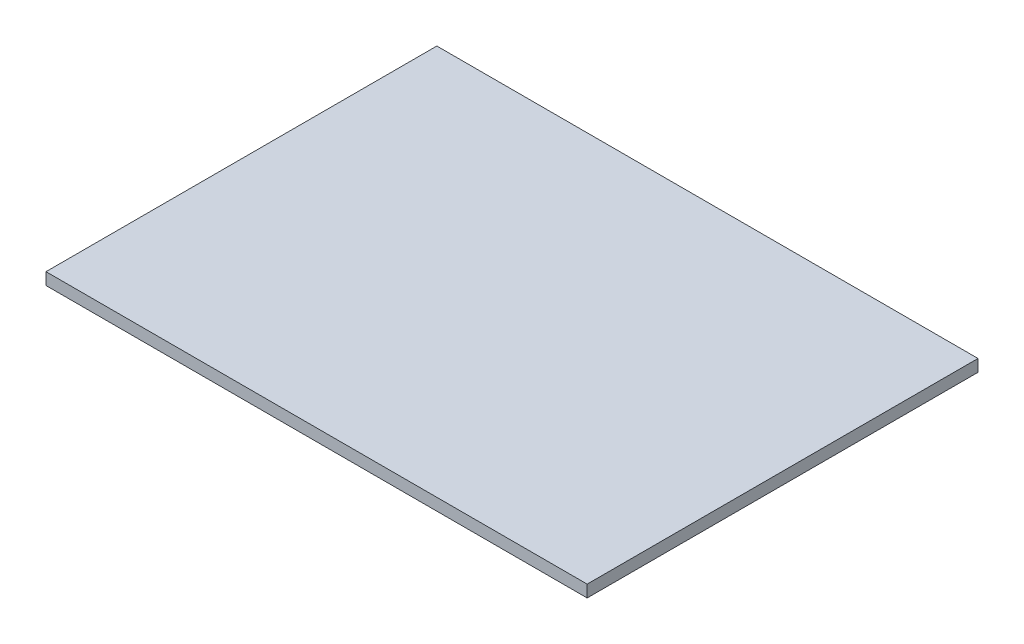
SolidWorks part; units mm, degrees
ref_plane "Front Plane" through (0, 0, 0) normal (0, 0, 1) x (1, 0, 0)
ref_plane "Top Plane" through (0, 0, 0) normal (0, 1, 0) x (1, 0, 0)
ref_plane "Right Plane" through (0, 0, 0) normal (1, 0, 0) x (0, 0, -1)
sketch "Sketch1" plane through (0, 0, 0) normal (0, 1, 0) x (1, 0, 0)
  line L1 (0, 0) -> (90, 0)
  line L2 (0, 0) -> (0, 65)
  line L3 (0, 65) -> (90, 65)
  line L4 (90, 0) -> (90, 65)
  dimension "D1" = 65
  dimension "D2" = 90
extrude "Boss-Extrude1" add sketch "Sketch1" along normal blind 2
sketch "Sketch2" plane through (0, 0, 0) normal (0, -1, 0) x (1, 0, 0)
  circle A0 centre (87.5, -4.396) radius 1.25
